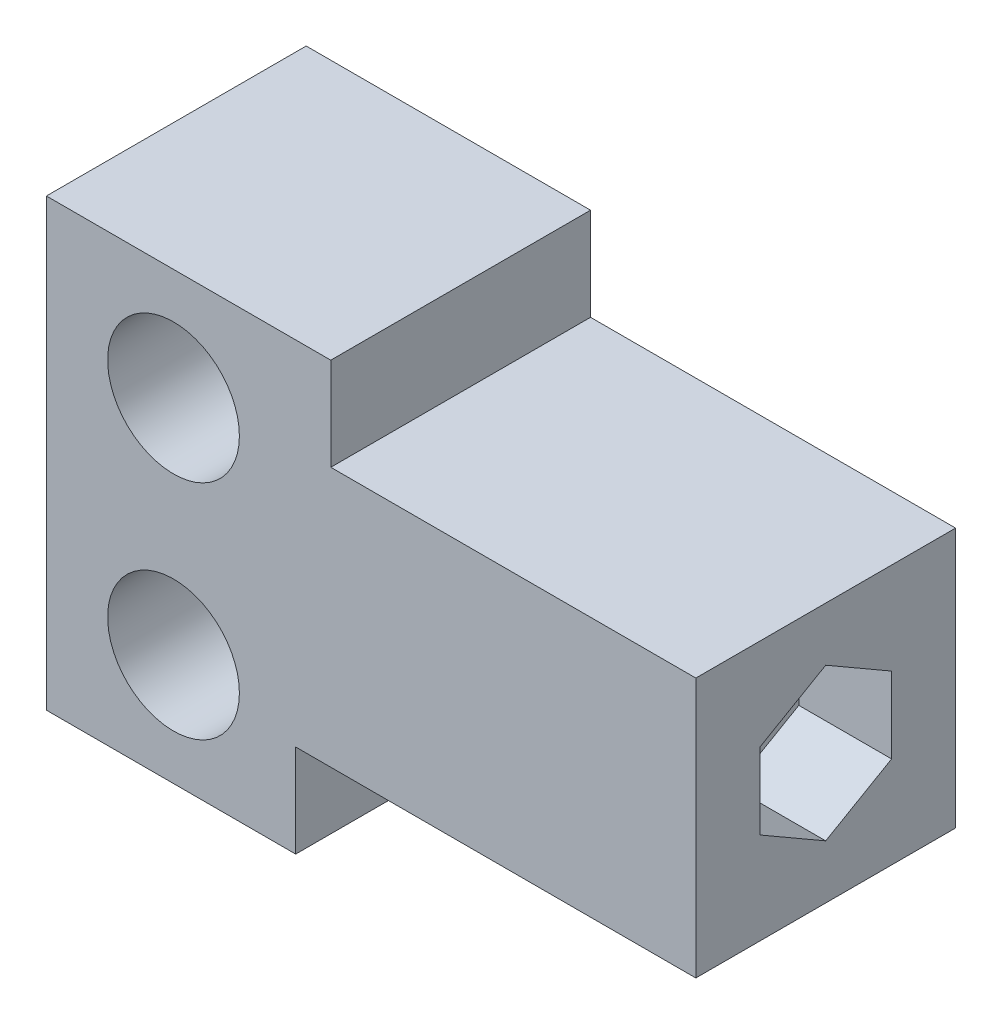
SolidWorks part; units mm, degrees
ref_plane "Front Plane" through (0, 0, 0) normal (0, 0, 1) x (1, 0, 0)
ref_plane "Top Plane" through (0, 0, 0) normal (0, 1, 0) x (1, 0, 0)
ref_plane "Right Plane" through (0, 0, 0) normal (1, 0, 0) x (0, 0, -1)
sketch "Esquisse1" plane through (0, 0, 0) normal (1, 0, 0) x (0, 0, -1)
  line L1 (-7, 7) -> (7, 7)
  line L2 (-7, 7) -> (-7, -7)
  line L3 (-7, -7) -> (7, -7)
  line L4 (7, 7) -> (7, -7)
  line L5 (-7, 7) -> (7, -7) construction
  line L6 (-7, -7) -> (7, 7) construction
  point P0 (0, 0)
extrude "Boss.-Extru.1" add sketch "Esquisse1" along normal blind 35
sketch "Esquisse2" plane through (0, 0, 0) normal (-1, 0, 0) x (0, 0, 1)
  circle A0 centre (0, 0) radius 2
extrude "Enlèv. mat.-Extru.1" cut sketch "Esquisse2" against normal through all
sketch "Esquisse3" plane through (35, 0, 0) normal (1, 0, 0) x (0, 0, -1)
  line L1 (3.55, -2.0496) -> (3.55, 2.0496)
  line L2 (3.55, 2.0496) -> (0, 4.0992)
  line L3 (0, 4.0992) -> (-3.55, 2.0496)
  line L4 (-3.55, 2.0496) -> (-3.55, -2.0496)
  line L5 (-3.55, -2.0496) -> (0, -4.0992)
  line L6 (0, -4.0992) -> (3.55, -2.0496)
  circle A0 centre (0, 0) radius 3.55 construction
  dimension "D1" = 7.1
extrude "Enlèv. mat.-Extru.2" cut sketch "Esquisse3" against normal blind 5
sketch "Esquisse4" plane through (0, 7, 0) normal (0, 1, 0) x (1, 0, 0)
  line L0 (35, -7) -> (0, -7) construction
  line L1 (0, 7) -> (15.3257, 7)
  line L2 (0, 7) -> (0, -7)
  line L3 (0, -7) -> (15.3257, -7)
  line L4 (15.3257, 7) -> (15.3257, -7)
extrude "Boss.-Extru.2" add sketch "Esquisse4" along normal blind 5
sketch "Esquisse5" plane through (0, -7, 0) normal (0, -1, 0) x (1, 0, 0)
  line L0 (35, -7) -> (0, -7) construction
  line L1 (0, 7) -> (13.4353, 7)
  line L2 (0, 7) -> (0, -7)
  line L3 (0, -7) -> (13.4353, -7)
  line L4 (13.4353, 7) -> (13.4353, -7)
extrude "Boss.-Extru.3" add sketch "Esquisse5" along normal blind 5
sketch "Esquisse6" plane through (0, 0, 7) normal (0, 0, 1) x (1, 0, 0)
  circle A0 centre (6.8505, 6) radius 1.5
  circle A1 centre (6.8505, -6) radius 1.5
  dimension "D1" = 3
extrude "Enlèv. mat.-Extru.3" cut sketch "Esquisse6" against normal through all
sketch "Esquisse7" plane through (0, 0, 7) normal (0, 0, 1) x (1, 0, 0)
  circle A0 centre (6.8505, 6) radius 3.55
  circle A1 centre (6.8505, -6) radius 3.55
extrude "Enlèv. mat.-Extru.4" cut sketch "Esquisse7" against normal blind 8
